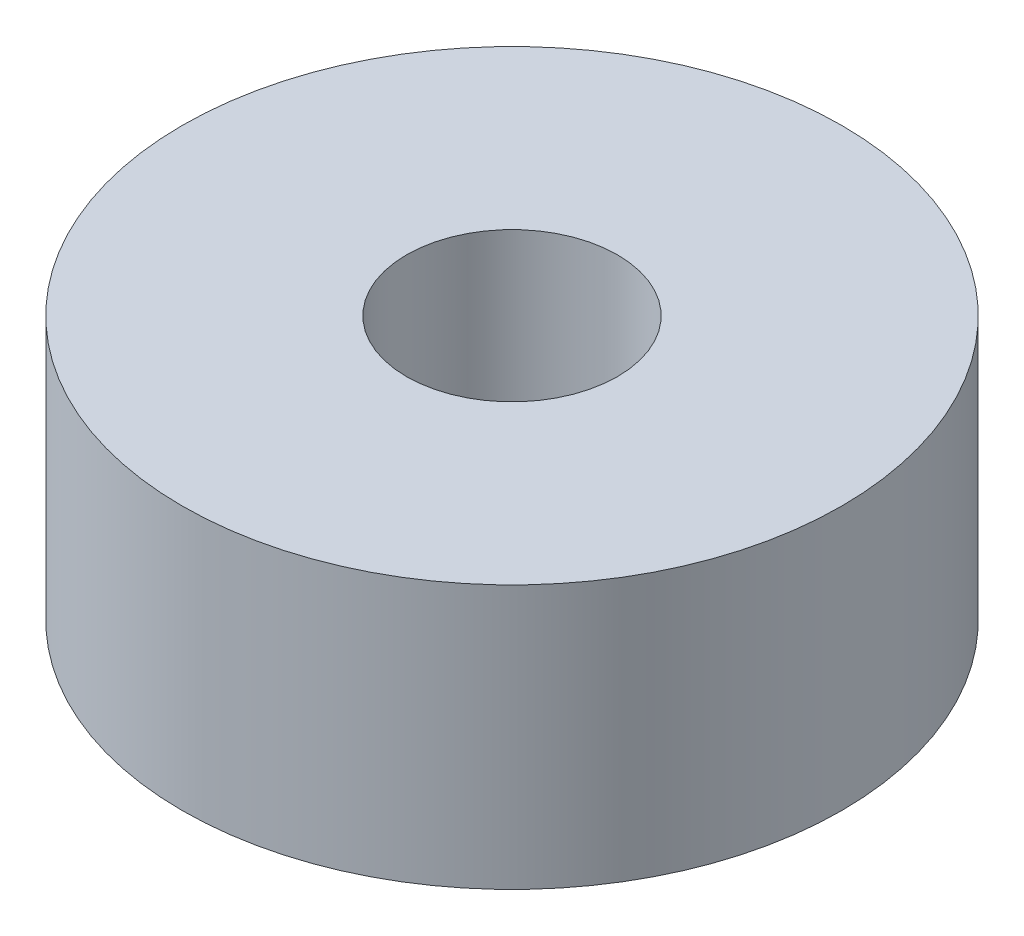
SolidWorks part; units mm, degrees
ref_plane "前视" through (0, 0, 0) normal (0, 0, 1) x (1, 0, 0)
ref_plane "上视" through (0, 0, 0) normal (0, 1, 0) x (1, 0, 0)
ref_plane "右视" through (0, 0, 0) normal (1, 0, 0) x (0, 0, -1)
sketch "草图1" plane through (0, 0, 0) normal (0, 1, 0) x (1, 0, 0)
  circle A0 centre (0, 0) radius 5
  circle A1 centre (0, 0) radius 1.6
  dimension "D1" = 3.2
  dimension "D2" = 10
extrude "凸台-拉伸1" add sketch "草图1" along normal blind 4
